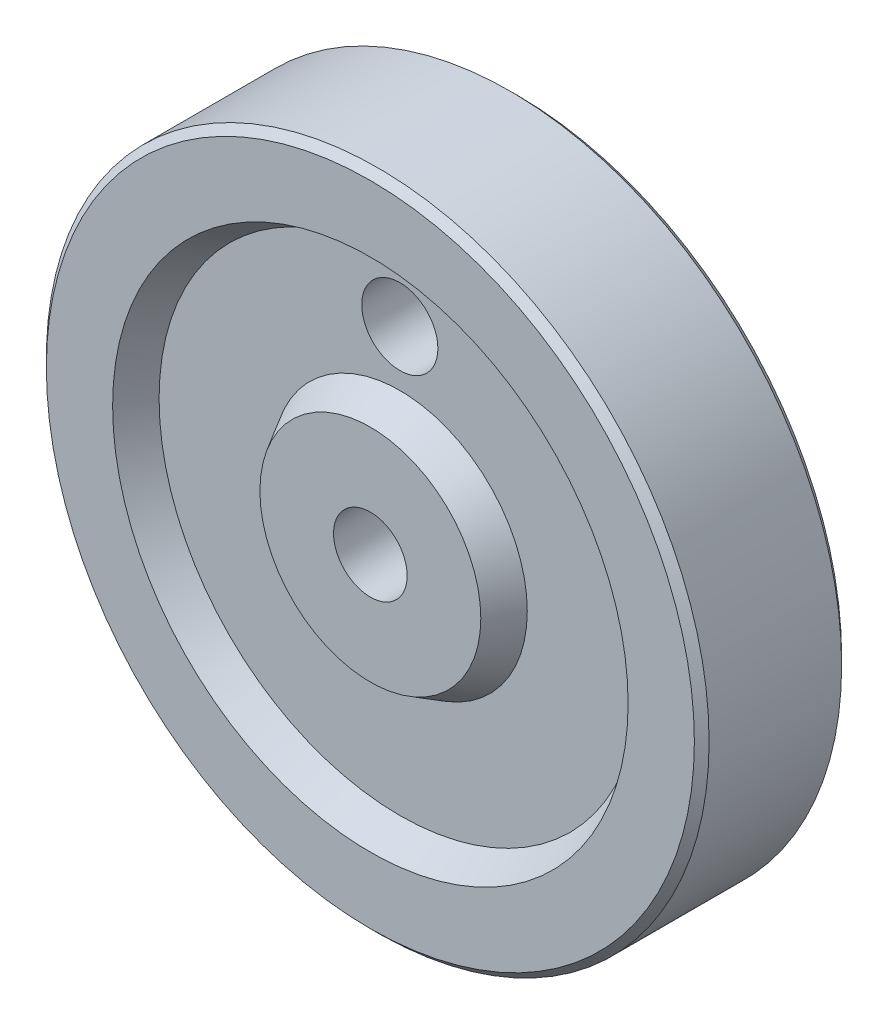
SolidWorks part; units mm, degrees
material "橡胶"
ref_plane "前视基准面" through (0, 0, 0) normal (0, 0, 1) x (1, 0, 0)
ref_plane "上视基准面" through (0, 0, 0) normal (0, 1, 0) x (1, 0, 0)
ref_plane "右视基准面" through (0, 0, 0) normal (1, 0, 0) x (0, 0, -1)
sketch "草图1" plane through (0, 0, 0) normal (0, 0, 1) x (1, 0, 0)
  circle A0 centre (0, 0) radius 225
  dimension "D1" = 450
extrude "凸台-拉伸1" add sketch "草图1" along normal mid plane 100
sketch "草图2" plane through (0, 0, 50) normal (0, 0, 1) x (1, 0, 0)
  circle A0 centre (0, 0) radius 25
  dimension "D1" = 50
extrude "切除-拉伸1" cut sketch "草图2" against normal through all
sketch "草图3" plane through (0, 0, 50) normal (0, 0, 1) x (1, 0, 0)
  circle A0 centre (0, 0) radius 75
  circle A1 centre (0, 0) radius 175
  dimension "D1" = 350
  dimension "D2" = 150
extrude "切除-拉伸3" cut sketch "草图3" against normal blind 20 draft 30
mirror "镜向1" about plane through (0, 0, 0) normal (0, 0, 1) of "切除-拉伸3"
chamfer "倒角1" distance 5 angle 45 2 edges at (225, 0, -50) (225, 0, 50)
sketch "草图4" plane through (0, 0, 30) normal (0, 0, 1) x (1, 0, 0)
  circle A0 centre (0, 124.095) radius 25.8524
extrude "切除-拉伸4" cut sketch "草图4" against normal through all
